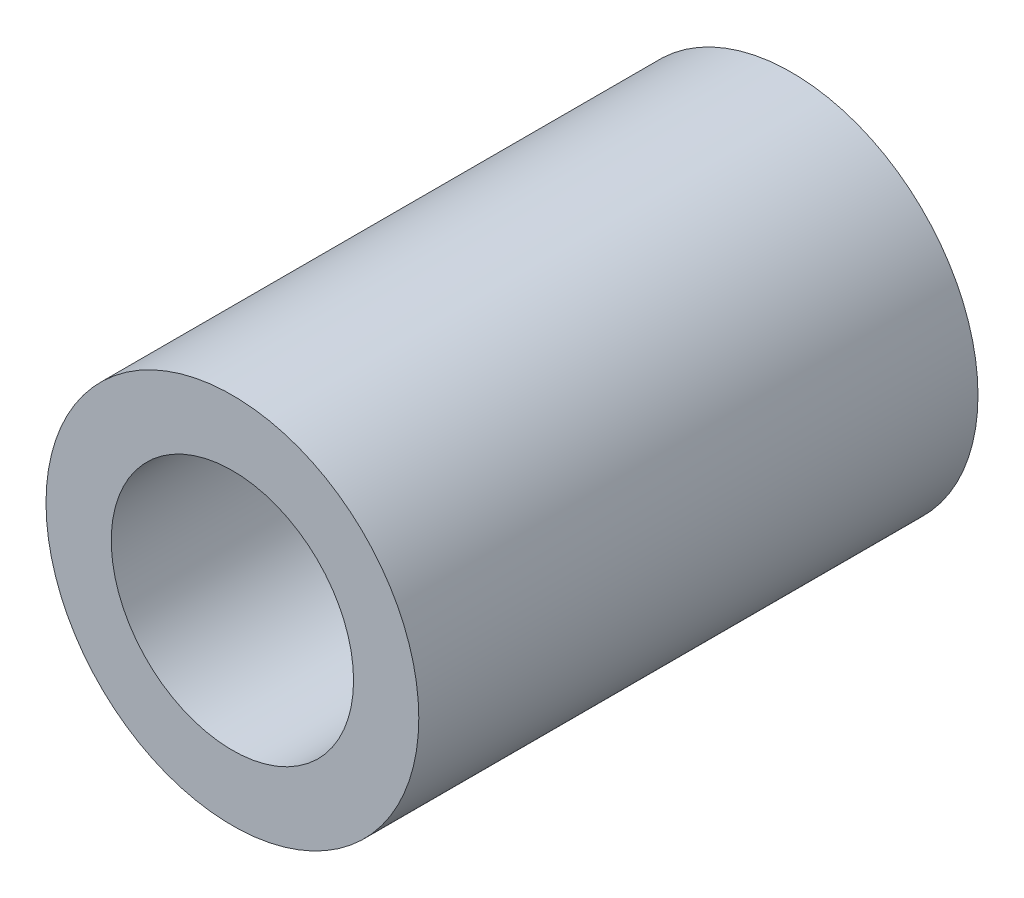
SolidWorks part; units mm, degrees
ref_plane "Plan de face" through (0, 0, 0) normal (0, 0, 1) x (1, 0, 0)
ref_plane "Plan de dessus" through (0, 0, 0) normal (0, 1, 0) x (1, 0, 0)
ref_plane "Plan de droite" through (0, 0, 0) normal (1, 0, 0) x (0, 0, -1)
sketch "Sketch1" plane through (0, 0, 0) normal (0, 0, 1) x (1, 0, 0)
  circle A0 centre (0, 0) radius 2.6
  circle A1 centre (0, 0) radius 4
  dimension "D1" = 5.2
  dimension "D2" = 8
extrude "Boss-Extrude1" add sketch "Sketch1" along normal blind 12
